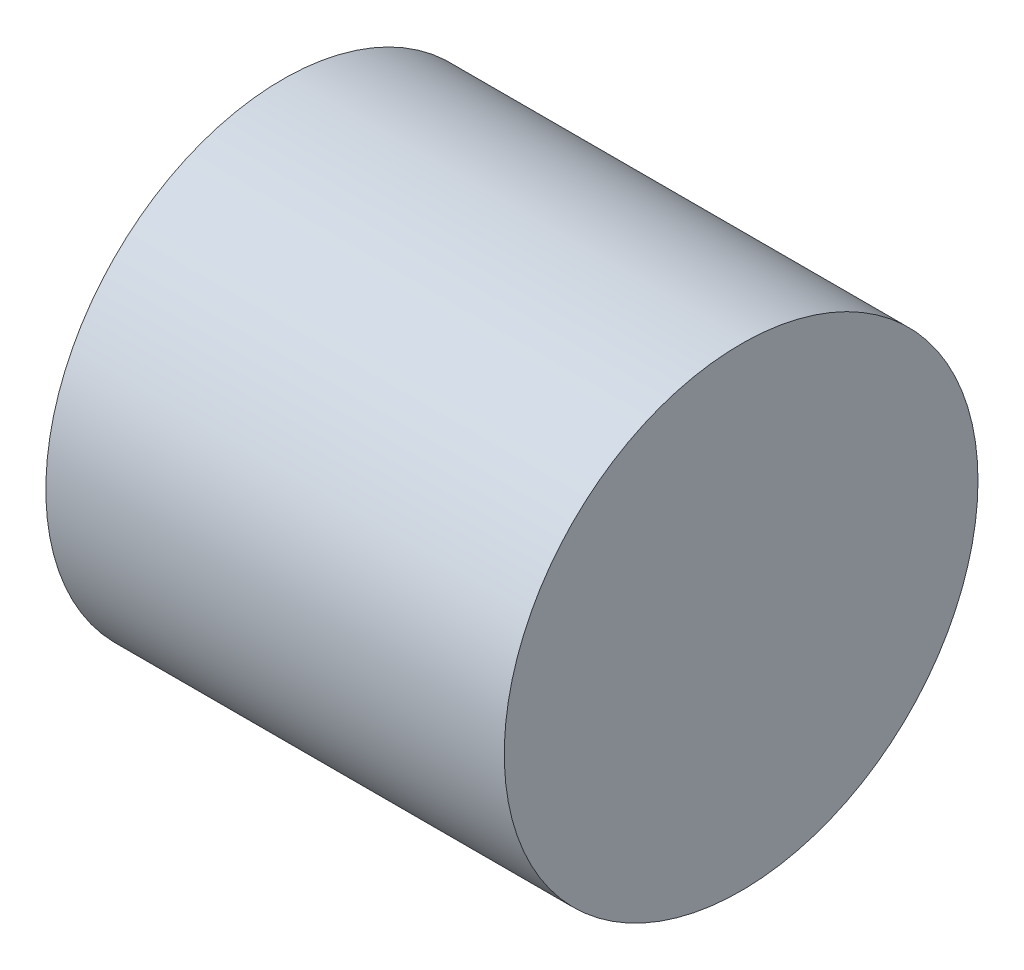
SolidWorks part; units mm, degrees
ref_plane "Front Plane" through (0, 0, 0) normal (0, 0, 1) x (1, 0, 0)
ref_plane "Top Plane" through (0, 0, 0) normal (0, 1, 0) x (1, 0, 0)
ref_plane "Right Plane" through (0, 0, 0) normal (1, 0, 0) x (0, 0, -1)
sketch "CurveSketch" plane through (0, 0, 0) normal (1, 0, 0) x (0, 0, -1)
  circle A0 centre (3.719, -5.983) radius 6.817
  dimension "D1" = 13.634
extrude "CurveBoss" add sketch "CurveSketch" along normal blind 13.193
